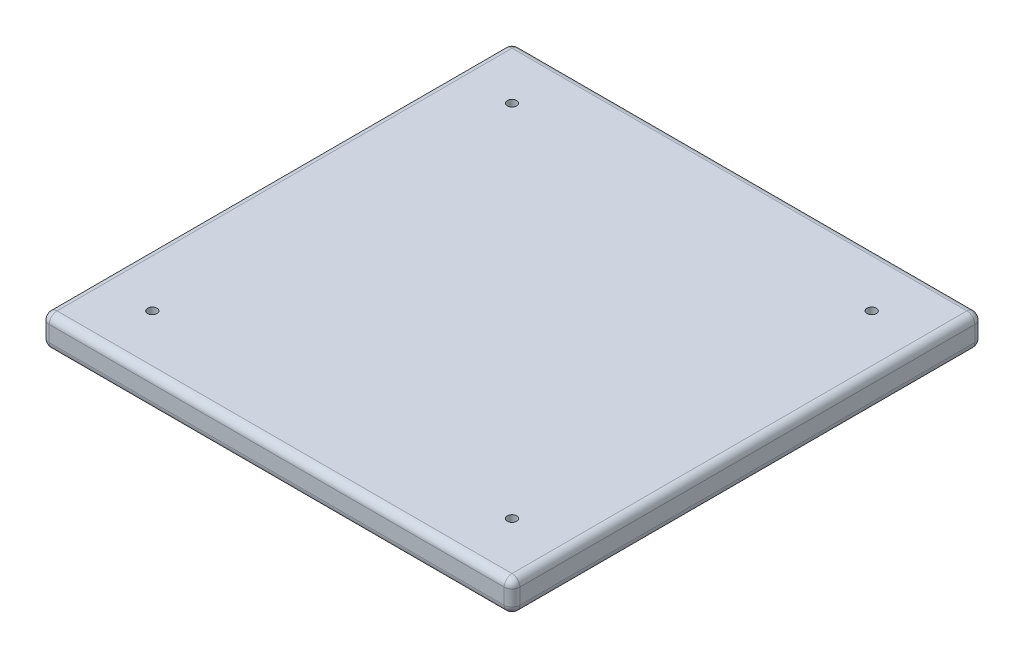
SolidWorks part; units mm, degrees
ref_plane "Front Plane" through (0, 0, 0) normal (0, 0, 1) x (1, 0, 0)
ref_plane "Top Plane" through (0, 0, 0) normal (0, 1, 0) x (1, 0, 0)
ref_plane "Right Plane" through (0, 0, 0) normal (1, 0, 0) x (0, 0, -1)
sketch "Sketch2" plane through (0, 0, 0) normal (0, 1, 0) x (1, 0, 0)
  line L1 (-75, 75) -> (75, 75)
  line L2 (-75, 75) -> (-75, -75)
  line L3 (-75, -75) -> (75, -75)
  line L4 (75, 75) -> (75, -75)
  line L5 (-75, 75) -> (75, -75) construction
  line L6 (-75, -75) -> (75, 75) construction
  point P0 (0, 0)
  dimension "D1" = 150
extrude "Boss-Extrude1" add sketch "Sketch2" along normal blind 10
sketch "Sketch3" plane through (0, 10, 0) normal (0, 1, 0) x (1, 0, 0)
  line L0 (0, 0) -> (15.7648, 0) construction
  line L1 (75, -75) -> (75, 75) construction
  line L2 (57.3223, 57.3223) -> (75, 75) construction
  circle A0 centre (57.3223, 57.3223) radius 1.5
  dimension "D1" = 45
  dimension "D3" = 3
  dimension "D2" = 25
extrude "Cut-Extrude1" cut sketch "Sketch3" against normal up to surface (10 mm away) up to face at (0, 0, 0)
ref_plane "Plane1" through (0, 0, 0) normal (0, 0, -1) x (-1, 0, 0)
ref_plane "Plane2" through (0, 0, 0) normal (-1, 0, 0) x (0, 0, 1)
mirror "Mirror1" about plane through (0, 0, 0) normal (0, 0, -1) of "Cut-Extrude1" second plane through (0, 0, 0) second plane normal (-1, 0, 0)
fillet "Fillet1" radius 2.5 12 edges at (0, 10, 75) (0, 0, 75) (0, 10, -75) (0, 0, -75) (-75, 5, -75) (-75, 10, 0) (-75, 5, 75) (-75, 0, 0) (75, 5, 75) (75, 10, 0) (75, 5, -75) (75, 0, 0)
